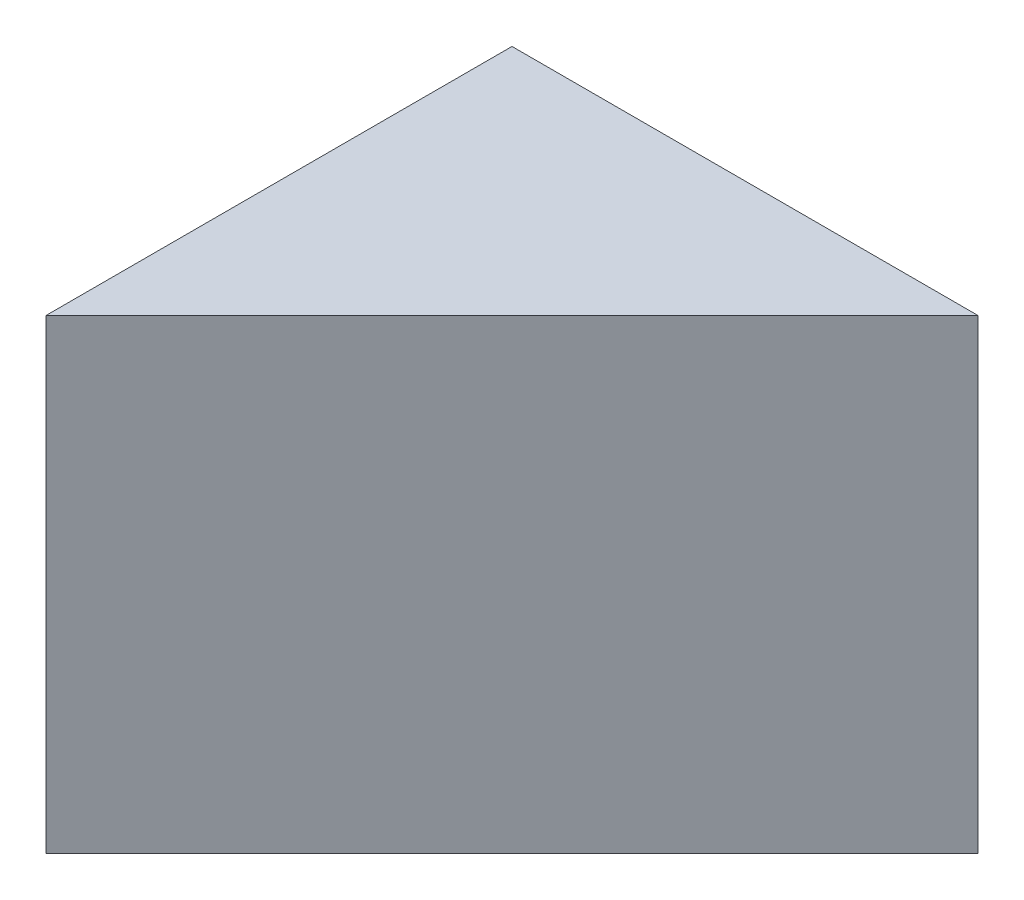
SolidWorks part; units mm, degrees
material "Glass"
ref_plane "Front Plane" through (0, 0, 0) normal (0, 0, 1) x (1, 0, 0)
ref_plane "Top Plane" through (0, 0, 0) normal (0, 1, 0) x (1, 0, 0)
ref_plane "Right Plane" through (0, 0, 0) normal (1, 0, 0) x (0, 0, -1)
sketch "Sketch1" plane through (0, 0, 0) normal (0, 1, 0) x (1, 0, 0)
  line L3 (12.5, 12.5) -> (-12.5, 12.5)
  line L4 (-12.5, -12.5) -> (-12.5, 12.5)
  line L5 (12.5, -12.5) -> (-12.5, 12.5) construction
  line L6 (12.5, 12.5) -> (-12.5, -12.5)
  point P0 (0, 0)
  point P6 (0, 0)
  point P7 (0, 0)
  dimension "D1" = 25
  dimension "D2" = 25
extrude "Boss-Extrude1" add sketch "Sketch1" along normal mid plane 25
